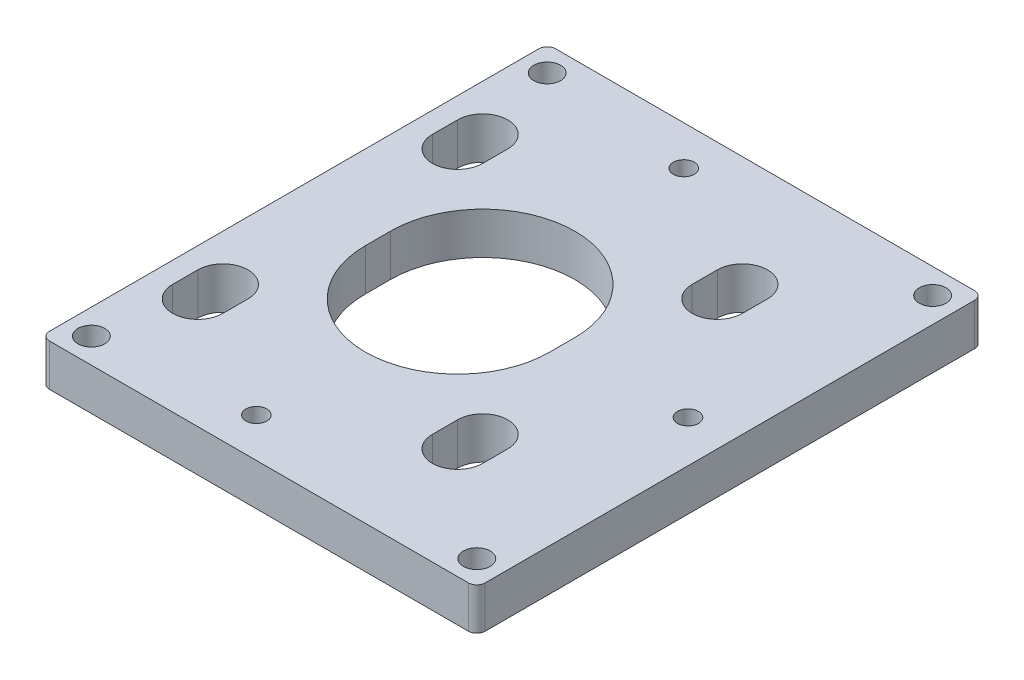
SolidWorks part; units mm, degrees
material "AISI 1045 Steel, cold drawn"
ref_plane "Front Plane" through (0, 0, 0) normal (0, 0, 1) x (1, 0, 0)
ref_plane "Top Plane" through (0, 0, 0) normal (0, 1, 0) x (1, 0, 0)
ref_plane "Right Plane" through (0, 0, 0) normal (1, 0, 0) x (0, 0, -1)
sketch "Sketch1" plane through (0, 0, 0) normal (0, 1, 0) x (1, 0, 0)
  line L0 (0, -1.5) -> (0, 1.5) construction
  line L1 (-11, -1.5) -> (-11, 1.5)
  line L2 (11, -1.5) -> (11, 1.5)
  line L3 (-15.5, 14) -> (-15.5, 17) construction
  line L4 (-18.5, 14) -> (-18.5, 17)
  line L5 (-12.5, 14) -> (-12.5, 17)
  line L6 (15.5, 14) -> (15.5, 17) construction
  line L7 (12.5, 14) -> (12.5, 17)
  line L8 (18.5, 14) -> (18.5, 17)
  line L9 (15.5, -17) -> (15.5, -14) construction
  line L10 (12.5, -17) -> (12.5, -14)
  line L11 (18.5, -17) -> (18.5, -14)
  line L12 (-15.5, -17) -> (-15.5, -14) construction
  line L13 (-18.5, -17) -> (-18.5, -14)
  line L14 (-12.5, -17) -> (-12.5, -14)
  line L15 (-15.5, 15.5) -> (15.5, 15.5) construction
  line L16 (-15.5, -15.5) -> (-15.5, 15.5) construction
  line L17 (21, -30.2) -> (21, 30.2) construction
  line L18 (-21, 30.2) -> (31, 30.2)
  line L19 (-21, 30.2) -> (-21, -30.2)
  line L20 (-21, -30.2) -> (31, -30.2)
  line L21 (31, 30.2) -> (31, -30.2)
  arc A0 (-11, -1.5) -> (11, -1.5) centre (0, -1.5) ccw
  arc A1 (11, 1.5) -> (-11, 1.5) centre (0, 1.5) ccw
  arc A2 (-18.5, 14) -> (-12.5, 14) centre (-15.5, 14) ccw
  arc A3 (-12.5, 17) -> (-18.5, 17) centre (-15.5, 17) ccw
  arc A4 (12.5, 14) -> (18.5, 14) centre (15.5, 14) ccw
  arc A5 (18.5, 17) -> (12.5, 17) centre (15.5, 17) ccw
  arc A6 (12.5, -17) -> (18.5, -17) centre (15.5, -17) ccw
  arc A7 (18.5, -14) -> (12.5, -14) centre (15.5, -14) ccw
  arc A8 (-18.5, -17) -> (-12.5, -17) centre (-15.5, -17) ccw
  arc A9 (-12.5, -14) -> (-18.5, -14) centre (-15.5, -14) ccw
  point P2 (0, 0)
  point P10 (-15.5, 15.5)
  point P16 (15.5, 15.5)
  point P23 (15.5, -15.5)
  point P30 (-15.5, -15.5)
  point P38 (0, 15.5)
  point P40 (-15.5, 0)
  point P43 (31, 0)
  dimension "D2" = 11
  dimension "D3" = 3
  dimension "D1" = 3
  dimension "D4" = 31
  dimension "D5" = 3
  dimension "D6" = 30.2
  dimension "D7" = 21
  dimension "D8" = 21
  dimension "D9" = 10
extrude "Boss-Extrude1" add sketch "Sketch1" along normal blind 5
hole_wizard "M3 Clearance Hole1" positions "Sketch2" profile "Sketch3" hole size "M3" standard "ANSI Metric" end condition through all
sketch "Sketch2" plane through (0, 5, 0) normal (0, 1, 0) x (1, 0, 0)
  line L0 (-21, -30.2) -> (31, -30.2) construction
  line L1 (-21, 30.2) -> (-21, -30.2) construction
  line L2 (31, -30.2) -> (31, 30.2) construction
  line L3 (31, 30.2) -> (-21, 30.2) construction
  point P0 (-18, -27.2)
  point P2 (28, -27.2)
  point P4 (28, 27.2)
  point P6 (-18, 27.2)
  dimension "D1" = 3
  dimension "D2" = 3
  dimension "D3" = 3
  dimension "D4" = 3
sketch "Sketch3" plane through (-18, 5, 27.2) normal (1, 0, 0) x (0, 0, 1)
  line L0 (0, 0) -> (0, 5)
  line L1 (0, 5) -> (1.6, 5)
  line L2 (1.6, 5) -> (1.6, 0)
  line L5 (1.6, 0) -> (0, 0)
  line L11 (0, -6.35) -> (0, 107.95) construction
  dimension "Thru Hole Dia." = 3.2
  dimension "Thru Hole Depth" = 5
hole_wizard "Tap Drill for M3x0.5 Tap1" positions "Sketch4" profile "Sketch5" hole size "M3x0.5" standard "ANSI Metric" end condition through all
sketch "Sketch4" plane through (0, 5, 0) normal (0, 1, 0) x (1, 0, 0)
  point P0 (26, 0)
  point P6 (0, 25.5)
  point P8 (0, -25.5)
  dimension "D1" = 26
  dimension "D2" = 25.5
  dimension "D3" = 25.5
sketch "Sketch5" plane through (26, 5, 0) normal (1, 0, 0) x (0, 0, 1)
  line L0 (0, 0) -> (0, 5)
  line L1 (0, 5) -> (1.25, 5)
  line L2 (1.25, 5) -> (1.25, 0)
  line L5 (1.25, 0) -> (0, 0)
  line L11 (0, -6.35) -> (0, 107.95) construction
  dimension "Thru Hole Dia." = 2.5
  dimension "Thru Hole Depth" = 5
fillet "Fillet1" radius 1 4 edges at (-21, 2.5, -30.2) (31, 2.5, -30.2) (-21, 2.5, 30.2) (31, 2.5, 30.2)
